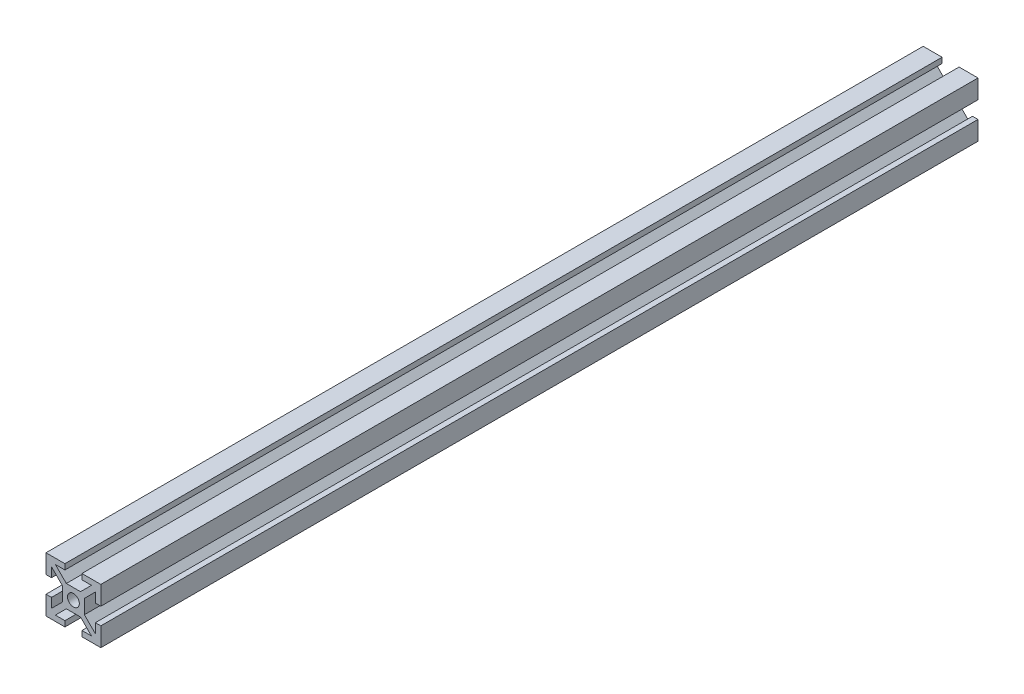
SolidWorks part; units mm, degrees
ref_plane "Plan de face" through (0, 0, 0) normal (0, 0, 1) x (1, 0, 0)
ref_plane "Plan de dessus" through (0, 0, 0) normal (0, 1, 0) x (1, 0, 0)
ref_plane "Plan de droite" through (0, 0, 0) normal (1, 0, 0) x (0, 0, -1)
sketch "Esquisse1" plane through (0, 0, 0) normal (0, 0, 1) x (1, 0, 0)
  line L0 (20, 13.1) -> (18, 13.1)
  line L1 (0, 0) -> (6.9, 0)
  line L2 (0, 0) -> (0, 6.9)
  line L3 (0, 20) -> (6.9, 20)
  line L4 (20, 0) -> (20, 6.9)
  line L5 (18, 13.1) -> (18, 16.5858)
  line L6 (0, 0) -> (20, 20) construction
  line L7 (14, 12.5858) -> (14, 10)
  line L8 (14, 12.5858) -> (18, 16.5858)
  line L9 (13.1, 20) -> (13.1, 18)
  line L10 (13.1, 18) -> (16.5858, 18)
  line L11 (12.5858, 14) -> (16.5858, 18)
  line L12 (12.5858, 14) -> (10, 14)
  line L13 (14, 7.4142) -> (14, 10)
  line L14 (14, 7.4142) -> (18, 3.4142)
  line L15 (18, 6.9) -> (18, 3.4142)
  line L16 (20, 6.9) -> (18, 6.9)
  line L17 (13.1, 2) -> (16.5858, 2)
  line L18 (12.5858, 6) -> (16.5858, 2)
  line L19 (13.1, 0) -> (13.1, 2)
  line L20 (12.5858, 6) -> (10, 6)
  line L21 (7.4142, 6) -> (10, 6)
  line L22 (7.4142, 6) -> (3.4142, 2)
  line L23 (6.9, 2) -> (3.4142, 2)
  line L24 (6.9, 0) -> (6.9, 2)
  line L25 (2, 6.9) -> (2, 3.4142)
  line L26 (6, 7.4142) -> (2, 3.4142)
  line L27 (0, 6.9) -> (2, 6.9)
  line L28 (6, 7.4142) -> (6, 10)
  line L29 (6, 12.5858) -> (6, 10)
  line L30 (6, 12.5858) -> (2, 16.5858)
  line L31 (2, 13.1) -> (2, 16.5858)
  line L32 (0, 13.1) -> (2, 13.1)
  line L33 (6.9, 18) -> (3.4142, 18)
  line L34 (7.4142, 14) -> (3.4142, 18)
  line L35 (6.9, 20) -> (6.9, 18)
  line L36 (7.4142, 14) -> (10, 14)
  line L37 (20, 13.1) -> (20, 20)
  line L38 (13.1, 20) -> (20, 20)
  line L39 (0, 13.1) -> (0, 20)
  line L40 (13.1, 0) -> (20, 0)
  circle A0 centre (10, 10) radius 2.15
  point P51 (10, 10)
  dimension "D2" = 4.3
  dimension "D1" = 20
  dimension "D3" = 2
  dimension "D4" = 6.2
  dimension "D5" = 6
  dimension "D6" = 2
  dimension "D7" = 4
extrude "Boss.-Extru.1" add sketch "Esquisse1" along normal blind 320
